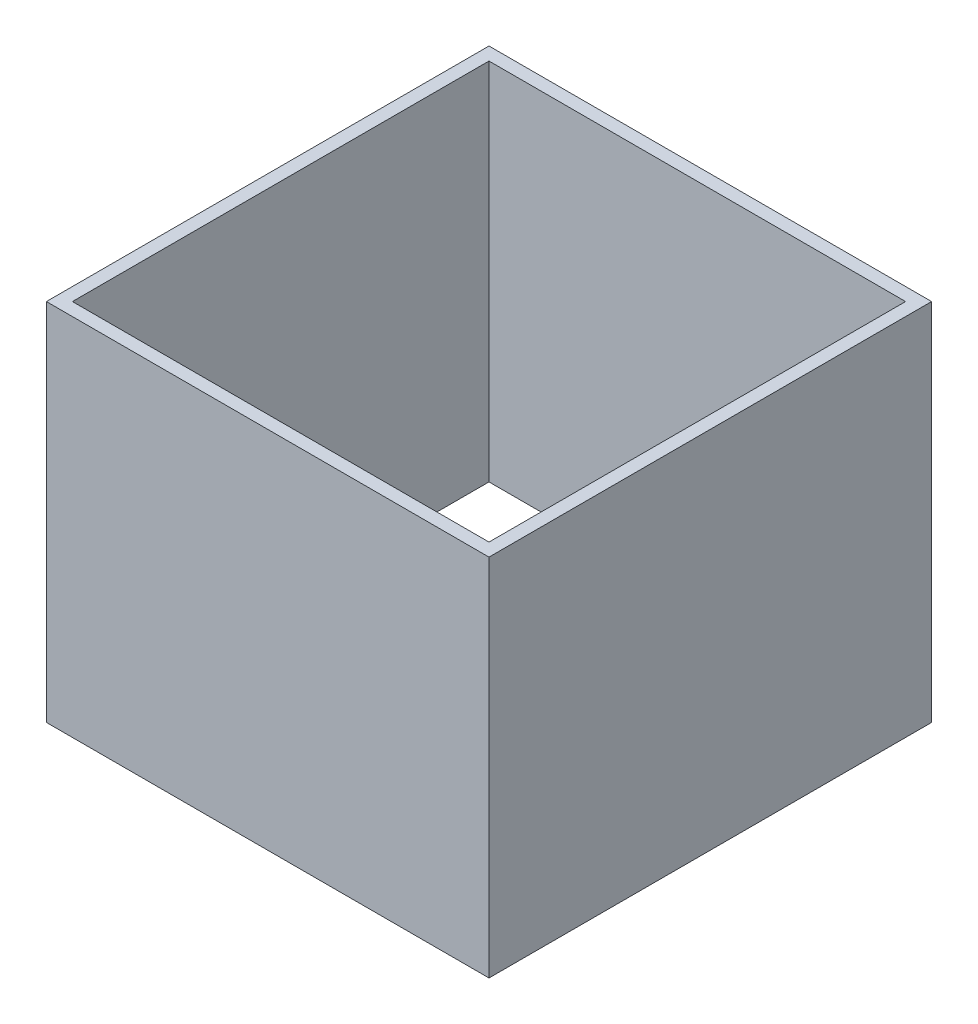
SolidWorks part; units mm, degrees
material "Glass"
ref_plane "Front Plane" through (0, 0, 0) normal (0, 0, 1) x (1, 0, 0)
ref_plane "Top Plane" through (0, 0, 0) normal (0, 1, 0) x (1, 0, 0)
ref_plane "Right Plane" through (0, 0, 0) normal (1, 0, 0) x (0, 0, -1)
sketch "Sketch1" plane through (0, 0, 0) normal (0, 1, 0) x (1, 0, 0)
  line L1 (-101.6, -101.6) -> (101.6, -101.6)
  line L2 (-101.6, -101.6) -> (-101.6, 101.6)
  line L3 (-101.6, 101.6) -> (101.6, 101.6)
  line L4 (101.6, -101.6) -> (101.6, 101.6)
  line L5 (-101.6, -101.6) -> (101.6, 101.6) construction
  line L6 (-101.6, 101.6) -> (101.6, -101.6) construction
  point P0 (0, 0)
  dimension "D1" = 203.2
  dimension "D2" = 203.2
extrude "Extrude-Thin1" add sketch "Sketch1" along normal blind 177.8 thin
